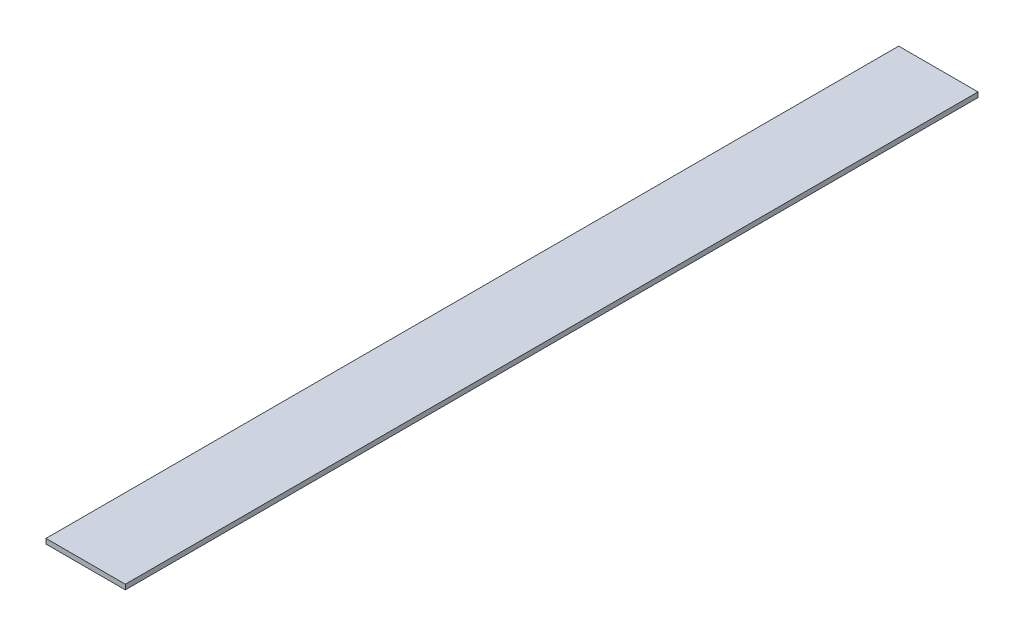
SolidWorks part; units mm, degrees
ref_plane "Front Plane" through (0, 0, 0) normal (0, 0, 1) x (1, 0, 0)
ref_plane "Top Plane" through (0, 0, 0) normal (0, 1, 0) x (1, 0, 0)
ref_plane "Right Plane" through (0, 0, 0) normal (1, 0, 0) x (0, 0, -1)
sketch "Sketch1" plane through (0, 0, 0) normal (0, 1, 0) x (1, 0, 0)
  line L1 (0, 0) -> (50.8, 0)
  line L2 (0, 0) -> (0, 546.1)
  line L3 (0, 546.1) -> (50.8, 546.1)
  line L4 (50.8, 0) -> (50.8, 546.1)
  line L5 (0, 0) -> (50.8, 0) construction
  dimension "D1" = 50.8
  dimension "D2" = 546.1
extrude "Boss-Extrude1" add sketch "Sketch1" along normal blind 3.175
